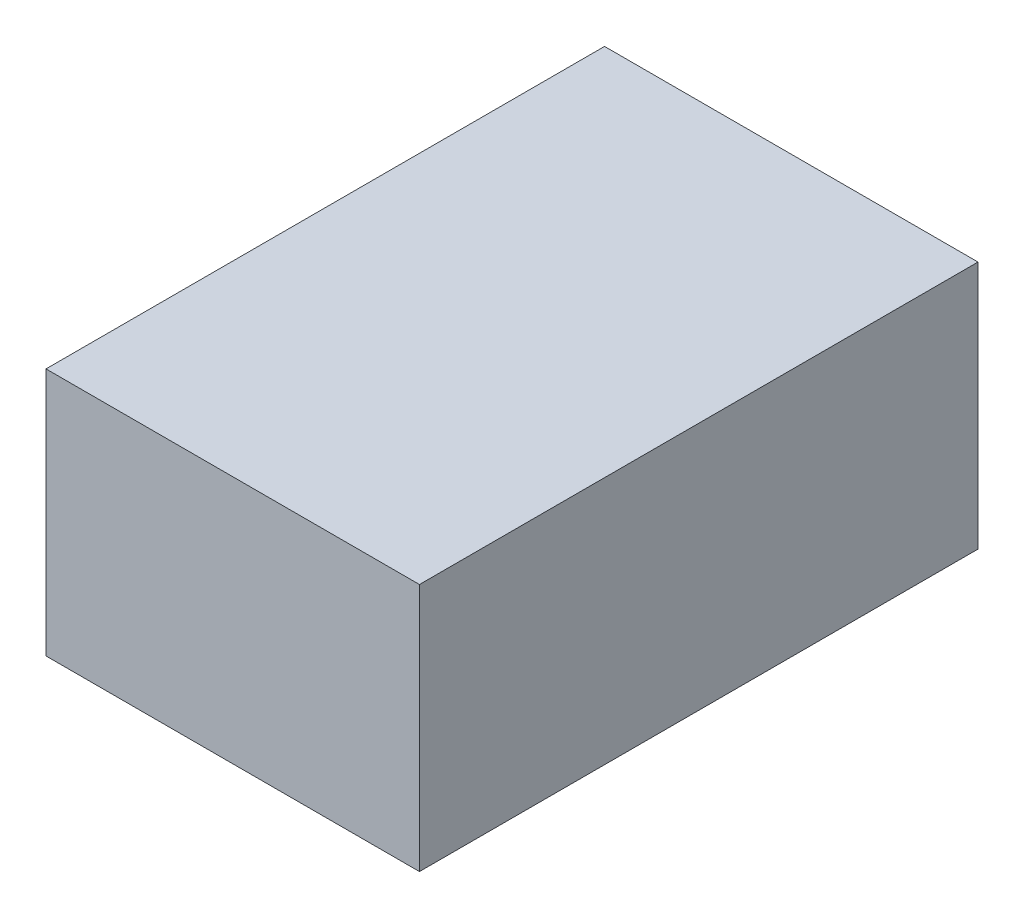
SolidWorks part; units mm, degrees
ref_plane "Front Plane" through (0, 0, 0) normal (0, 0, 1) x (1, 0, 0)
ref_plane "Top Plane" through (0, 0, 0) normal (0, 1, 0) x (1, 0, 0)
ref_plane "Right Plane" through (0, 0, 0) normal (1, 0, 0) x (0, 0, -1)
sketch "Sketch1" plane through (0, 0, 0) normal (0, 0, 1) x (1, 0, 0)
  line L1 (-33.9661, 22.6124) -> (33.9662, 22.6124)
  line L2 (-33.9661, 22.6124) -> (-33.9661, -22.6123)
  line L3 (-33.9661, -22.6123) -> (33.9662, -22.6123)
  line L4 (33.9662, 22.6124) -> (33.9662, -22.6123)
  line L5 (-33.9661, 22.6124) -> (33.9662, -22.6123) construction
  line L6 (-33.9661, -22.6123) -> (33.9662, 22.6124) construction
  point P0 (0, 0)
  dimension "D1" = 67.9323
  dimension "D2" = 45.2247
extrude "Extrude1" add sketch "Sketch1" against normal blind 101.6
sketch "Sketch3" plane through (0, 0, 0) normal (0, 0, 1) x (1, 0, 0)
  line L0 (0, 22.6124) -> (0, -22.6123) construction
  line L1 (33.9662, 22.6124) -> (-33.9661, 22.6124) construction
  line L2 (-33.9661, -22.6123) -> (33.9662, -22.6123) construction
  line L3 (33.9662, 0) -> (-33.9661, 0) construction
  line L4 (33.9662, -22.6123) -> (33.9662, 22.6124) construction
  line L5 (-33.9661, 22.6124) -> (-33.9661, -22.6123) construction
ref_plane "Plane1" through (0, 0, 0) normal (-1, 0, 0) x (0, 0, 1)
